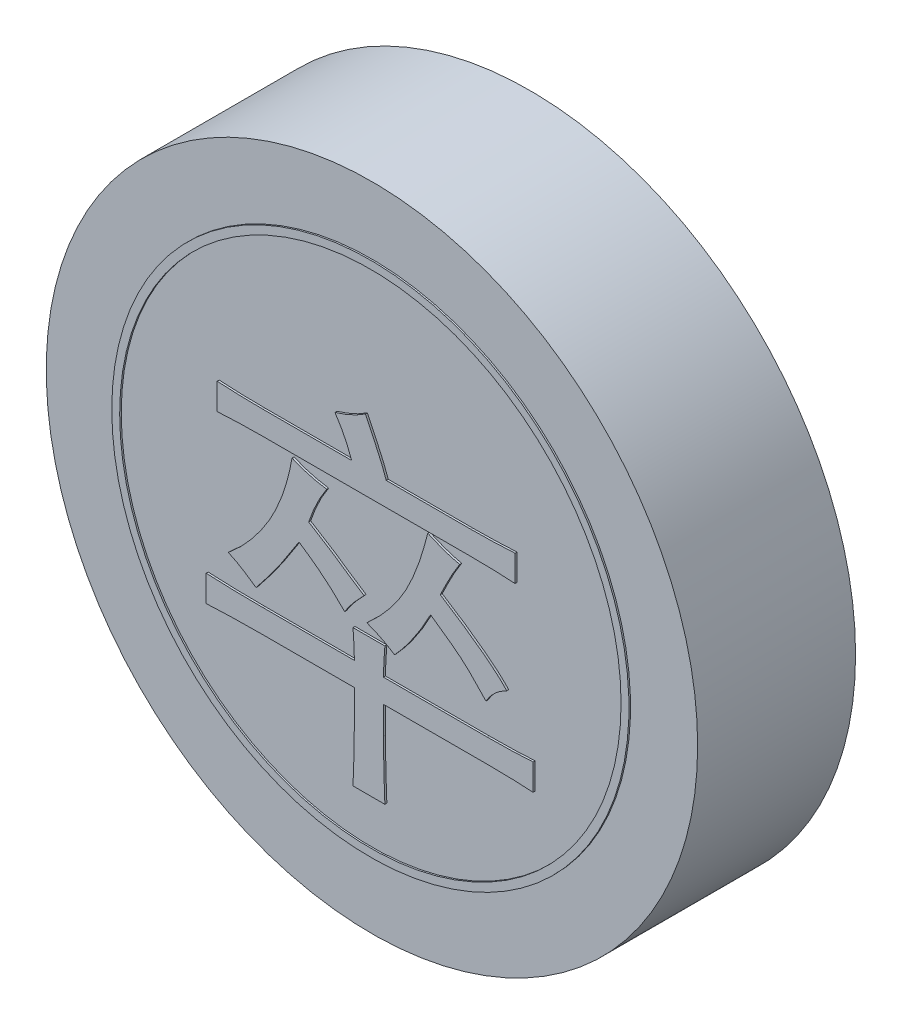
SolidWorks part; units mm, degrees
ref_plane "前视基准面" through (0, 0, 0) normal (0, 0, 1) x (1, 0, 0)
ref_plane "上视基准面" through (0, 0, 0) normal (0, 1, 0) x (1, 0, 0)
ref_plane "右视基准面" through (0, 0, 0) normal (1, 0, 0) x (0, 0, -1)
other "Configuration Table"
sketch "草图1" plane through (0, 0, 0) normal (0, 0, 1) x (1, 0, 0)
  circle A0 centre (0, 0) radius 16.5
  dimension "D1" = 33
extrude "Diameter33_Height8" add sketch "草图1" against normal blind 8
sketch "草图2" plane through (0, 0, 0) normal (0, 0, 1) x (1, 0, 0)
  text T0 "卒" font "SimHei" height 12
extrude "Character_卒" add sketch "草图2" along normal blind 0.1
sketch "草图3" plane through (0, 0, 0) normal (0, 0, 1) x (1, 0, 0)
  circle A0 centre (0, 0) radius 13.1
  circle A1 centre (0, 0) radius 12.7
extrude "Ink_ring" add sketch "草图3" along normal blind 0.08
